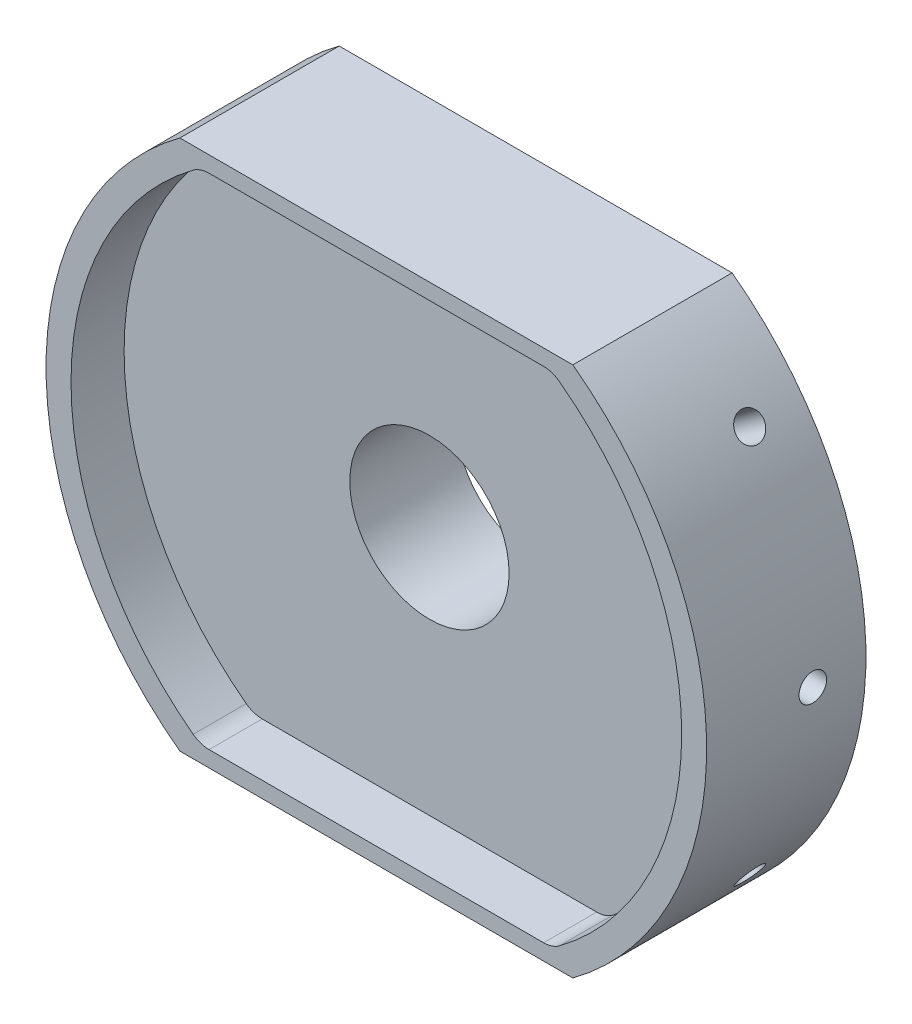
SolidWorks part; units mm, degrees
material "ABS PC"
ref_plane "Ön Düzlem" through (0, 0, 0) normal (0, 0, 1) x (1, 0, 0)
ref_plane "Üst Düzlem" through (0, 0, 0) normal (0, 1, 0) x (1, 0, 0)
ref_plane "Sağ Düzlem" through (0, 0, 0) normal (1, 0, 0) x (0, 0, -1)
sketch "Çizim1" plane through (0, 0, 0) normal (0, 0, 1) x (1, 0, 0)
  line L0 (0, 0) -> (0, 47) construction
  line L1 (31.5, 47) -> (-31.5, 47)
  line L2 (0, -47) -> (0, 0) construction
  line L3 (31.5, -47) -> (-31.5, -47)
  arc A0 (-34.5, 46) -> (-34.5, -46) centre (0, 0) ccw
  circle A1 centre (0, 0) radius 62.2
  arc A2 (34.5, -46) -> (34.5, 46) centre (0, 0) ccw
  arc A3 (31.5, -47) -> (34.5, -46) centre (31.5, -42) ccw
  arc A4 (-31.5, -47) -> (-34.5, -46) centre (-31.5, -42) cw
  arc A5 (31.5, 47) -> (34.5, 46) centre (31.5, 42) cw
  arc A6 (-31.5, 47) -> (-34.5, 46) centre (-31.5, 42) ccw
  point P8 (0, 47)
  point P13 (0, -47)
  dimension "D1" = 115
  dimension "D2" = 124.4
  dimension "D4" = 5
  dimension "D3" = 47
extrude "Yükseklik-Ekstrüzyon3" add sketch "Çizim1" along normal blind 10
sketch "Çizim2" plane through (0, 0, 0) normal (0, 0, -1) x (-1, 0, 0)
  circle A0 centre (0, 0) radius 62.2
  dimension "D1" = 124.4
extrude "Yükseklik-Ekstrüzyon4" add sketch "Çizim2" along normal blind 20
ref_plane "Düzlem1" through (0, 62.2, 0) normal (0, 1, 0) x (1, 0, 0)
sketch "Çizim12" plane through (0, 0, 10) normal (0, 0, 1) x (1, 0, 0)
  line L0 (0, 47) -> (0, 50) construction
  line L1 (31.5, 47) -> (-31.5, 47) construction
  line L2 (-50.6037, 50) -> (50.6037, 50)
  line L3 (-50.6037, 50) -> (-3.0386, 77.0965)
  line L4 (-3.0386, 77.0965) -> (50.6037, 50)
  line L5 (0, -47) -> (0, -50) construction
  line L6 (-31.5, -47) -> (31.5, -47) construction
  line L7 (36.9978, -50) -> (-36.9978, -50)
  line L8 (-36.9978, -50) -> (-1.1763, -79.4825)
  line L9 (-1.1763, -79.4825) -> (36.9978, -50)
  circle A2 centre (0, 0) radius 62.2 construction
  circle A3 centre (0, 0) radius 15
  point P7 (0, 50)
  point P18 (0, -50)
  dimension "D1" = 3
  dimension "D3" = 30
  dimension "D2" = 3
extrude "Kes-Ekstrüzyon1" cut sketch "Çizim12" against normal through all
ref_plane "Düzlem2" through (62.2, 0, 0) normal (1, 0, 0) x (0, 0, -1)
sketch "Çizim14" plane through (62.2, 0, 0) normal (1, 0, 0) x (0, 0, -1)
  line L0 (20, 0) -> (10, 0) construction
  line L1 (20, -50) -> (20, 50) construction
  point P1 (10, 0)
  point P7 (10, 0)
  dimension "D1" = 10
hole_wizard "M5x0.8 Helisarmal İçin Dişli Delik1" positions "Çizim14" profile "Çizim15" tap size "M5x0.8" standard "Helicoil® Metric"
sketch "Çizim15" plane through (62.2, 0, -10) normal (0, 1, 0) x (0, 0, -1)
  line L0 (0, 0) -> (0, 15.1622)
  line L1 (0, 15.1622) -> (2.6, 13.6)
  line L2 (2.6, 13.6) -> (2.6, 0)
  line L5 (2.6, 0) -> (0, 0)
  line L10 (0, 15.1622) -> (-2.6, 13.6) construction
  line L11 (0, -6.35) -> (0, 107.95) construction
  dimension "Tap Drill Dia." = 5.2
  dimension "Tap Drill Depth" = 13.6
  dimension "Drill Angle" = 118
cosmetic thread "Delik Dişi1" parameters "D1"=5.8, "D2"=6.145
pattern_circular "Dairesel Kaplama1" count 10 over 360 about axis through (0, 0, 10) along (0, 0, 1) skipping 2, 3, 7, 8 of "M5x0.8 Helisarmal İçin Dişli Delik1"
cosmetic thread "Delik Dişi2" parameters "D1"=5.8, "D2"=6.145
cosmetic thread "Delik Dişi3" parameters "D1"=5.8, "D2"=6.145
cosmetic thread "Delik Dişi4" parameters "D1"=5.8, "D2"=6.145
cosmetic thread "Delik Dişi5" parameters "D1"=5.8, "D2"=6.145
cosmetic thread "Delik Dişi6" parameters "D1"=5.8, "D2"=6.145
